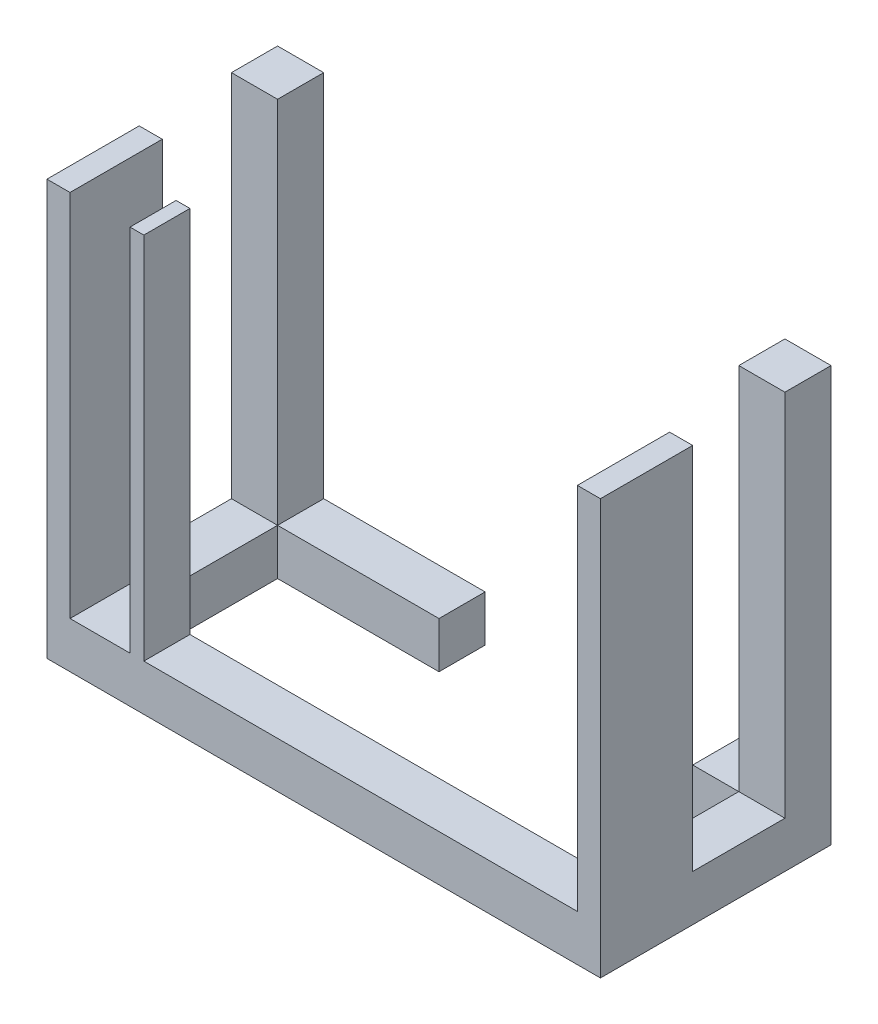
SolidWorks part; units mm, degrees
ref_plane "前视基准面" through (0, 0, 0) normal (0, 0, 1) x (1, 0, 0)
ref_plane "上视基准面" through (0, 0, 0) normal (0, 1, 0) x (1, 0, 0)
ref_plane "右视基准面" through (0, 0, 0) normal (1, 0, 0) x (0, 0, -1)
sketch "草图1" plane through (0, 0, 0) normal (0, 1, 0) x (1, 0, 0)
  line L0 (-50, 15) -> (50, 15)
  line L1 (-60, -25) -> (60, -25)
  line L2 (-60, -25) -> (-60, 25)
  line L3 (-60, 25) -> (60, 25)
  line L4 (60, -25) -> (60, 25)
  line L5 (-60, -25) -> (60, 25) construction
  line L6 (-60, 25) -> (60, -25) construction
  line L7 (50, -15) -> (50, 15)
  line L8 (-50, -15) -> (50, -15)
  line L9 (-50, -15) -> (-50, 15)
  point P0 (0, 0)
  dimension "D1" = 50
  dimension "D2" = 120
  dimension "D3" = 10
extrude "凸台-拉伸1" add sketch "草图1" along normal blind 10
sketch "草图2" plane through (0, 10, 0) normal (0, 1, 0) x (1, 0, 0)
  line L0 (0, 8.5702) -> (0, -11.5091) construction
  line L1 (60, -25) -> (55, -25)
  line L2 (60, -25) -> (60, -5)
  line L3 (60, -5) -> (55, -5)
  line L4 (55, -25) -> (55, -5)
  line L5 (-60, -25) -> (-55, -25)
  line L6 (-60, -25) -> (-60, -5)
  line L7 (-60, -5) -> (-55, -5)
  line L8 (-55, -25) -> (-55, -5)
  line L9 (50, 15) -> (-50, 15) construction
  line L10 (-60, 25) -> (-50, 25)
  line L11 (-60, 25) -> (-60, 15)
  line L12 (-60, 15) -> (-50, 15)
  line L13 (-50, 25) -> (-50, 15)
  line L14 (60, 25) -> (50, 25)
  line L15 (60, 25) -> (60, 15)
  line L16 (60, 15) -> (50, 15)
  line L17 (50, 25) -> (50, 15)
  line L18 (-60, -25) -> (60, -25) construction
  line L19 (-39, -25) -> (-42, -25)
  line L20 (-39, -25) -> (-39, -15)
  line L21 (-39, -15) -> (-42, -15)
  line L22 (-42, -25) -> (-42, -15)
  line L23 (-50, -15) -> (50, -15) construction
  dimension "D1" = 5
  dimension "D2" = 20
  dimension "D3" = 3
  dimension "D4" = 13
extrude "凸台-拉伸2" add sketch "草图2" along normal blind 80
sketch "草图3" plane through (0, 0, 0) normal (0, -1, 0) x (1, 0, 0)
  line L0 (50, -15) -> (-50, -15) construction
  line L1 (40, -15) -> (-15, -15)
  line L2 (40, -15) -> (40, -25)
  line L3 (40, -25) -> (-15, -25)
  line L4 (-15, -15) -> (-15, -25)
  line L5 (60, -25) -> (-60, -25) construction
  line L6 (60, 25) -> (60, -25) construction
  dimension "D1" = 20
  dimension "D2" = 55
extrude "切除-拉伸1" cut sketch "草图3" against normal through all
